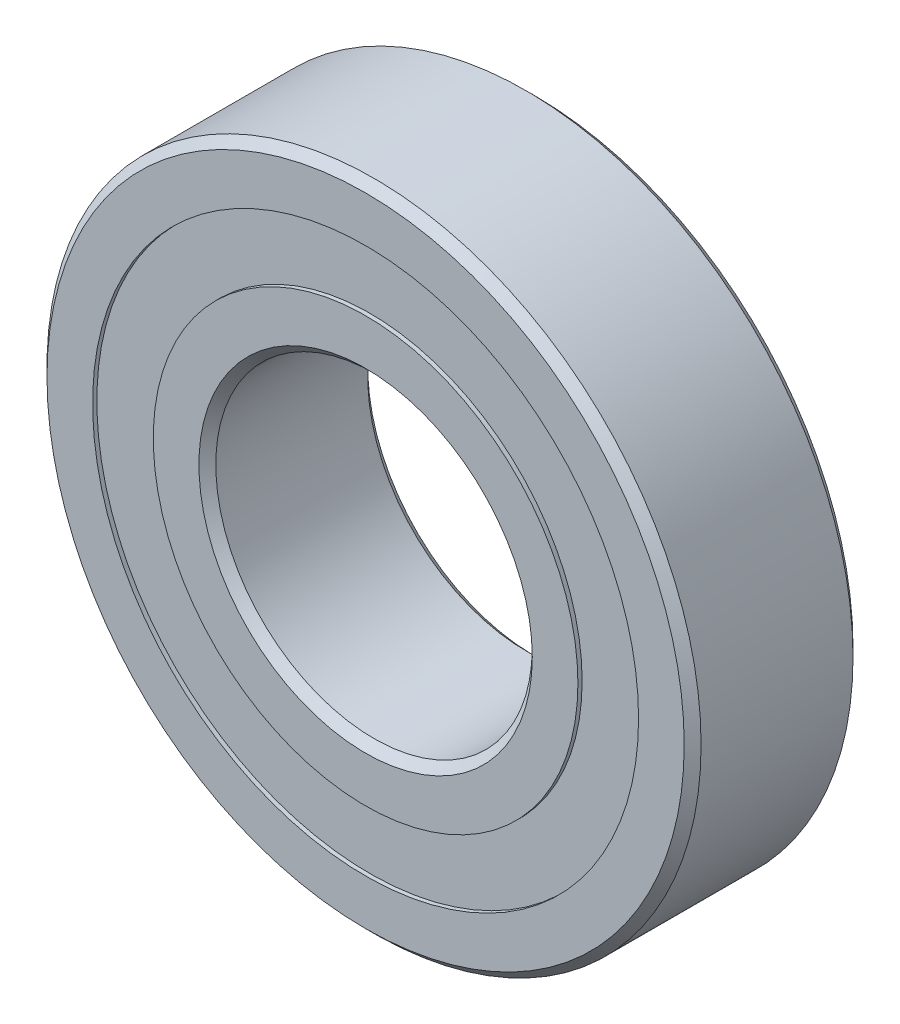
SolidWorks part; units mm, degrees
ref_plane "Front Plane" through (0, 0, 0) normal (0, 0, 1) x (1, 0, 0)
ref_plane "Top Plane" through (0, 0, 0) normal (0, 1, 0) x (1, 0, 0)
ref_plane "Right Plane" through (0, 0, 0) normal (1, 0, 0) x (0, 0, -1)
sketch "Sketch1" plane through (0, 0, 0) normal (0, 0, 1) x (1, 0, 0)
  circle A0 centre (0, 0) radius 31 construction
  circle A1 centre (0, 0) radius 15 construction
  dimension "OD" = 62
  dimension "ID" = 30
sketch "Sketch2" plane through (0, 0, 0) normal (1, 0, 0) x (0, 0, -1)
  line L0 (-8, 0) -> (8, 0) construction
  line L1 (0, 31) -> (0, -31) construction
  line L2 (7.2, 31) -> (-7.2, 31) construction
  line L3 (-7.2, 31) -> (-8, 30.2) construction
  line L4 (-8, 30.2) -> (-8, 25.875) construction
  line L5 (-8, 25.875) -> (-3.5556, 25.875) construction
  line L6 (8, 25.875) -> (3.5556, 25.875) construction
  line L7 (8, 30.2) -> (8, 25.875) construction
  line L8 (7.2, 31) -> (8, 30.2) construction
  line L9 (0, 31) -> (0, 23) construction
  line L10 (0, 23) -> (0, 15) construction
  line L11 (8, 23) -> (-8, 23) construction
  line L12 (-8, 15.8) -> (-8, 20.125) construction
  line L13 (-7.2, 15) -> (-8, 15.8) construction
  line L14 (7.2, 15) -> (-7.2, 15) construction
  line L15 (7.2, 15) -> (8, 15.8) construction
  line L16 (8, 15.8) -> (8, 20.125) construction
  line L17 (8, 20.125) -> (3.5556, 20.125) construction
  line L18 (-8, 20.125) -> (-3.5556, 20.125) construction
  line L19 (-8, 15) -> (-8, -15) construction
  line L20 (8, 31) -> (8, -31) construction
  arc A0 (-3.5556, 25.875) -> (3.5556, 25.875) centre (0, 23) cw construction
  arc A1 (-3.5556, 20.125) -> (3.5556, 20.125) centre (0, 23) ccw construction
  point P14 (0, 15)
  point P18 (0, 23)
  dimension "Approx. Ball Dia." = 9.145
  dimension "D1" = 45
  dimension "D2" = 0.8
  dimension "D3" = 7.1111
  dimension "D4" = 2.875
  dimension "Width" = 16
  dimension "For Shaft Diameter" = 30
  dimension "For Housing ID" = 62
sketch "Sketch3" plane through (0, 0, 0) normal (1, 0, 0) x (0, 0, -1)
  line L0 (-8, 30.2) -> (-8, 25.875) construction
  line L1 (-7.2, 31) -> (-8, 30.2) construction
  line L2 (7.2, 31) -> (-7.2, 31) construction
  line L3 (7.2, 31) -> (8, 30.2) construction
  line L4 (8, 30.2) -> (8, 25.875) construction
  line L5 (8, 25.875) -> (3.5556, 25.875) construction
  line L6 (-8, 25.875) -> (-3.5556, 25.875) construction
  line L7 (-8, 30.2) -> (-8, 25.875)
  line L8 (-7.2, 31) -> (-8, 30.2)
  line L9 (7.2, 31) -> (-7.2, 31)
  line L10 (7.2, 31) -> (8, 30.2)
  line L11 (8, 30.2) -> (8, 25.875)
  line L12 (8, 25.875) -> (3.5556, 25.875)
  line L13 (-8, 25.875) -> (-3.5556, 25.875)
  line L14 (-8, 15.8) -> (-8, 20.125) construction
  line L15 (-7.2, 15) -> (-8, 15.8) construction
  line L16 (7.2, 15) -> (-7.2, 15) construction
  line L17 (7.2, 15) -> (8, 15.8) construction
  line L18 (8, 15.8) -> (8, 20.125) construction
  line L19 (8, 20.125) -> (3.5556, 20.125) construction
  line L20 (-8, 20.125) -> (-3.5556, 20.125) construction
  line L21 (-8, 15.8) -> (-8, 20.125)
  line L22 (-7.2, 15) -> (-8, 15.8)
  line L23 (7.2, 15) -> (-7.2, 15)
  line L24 (7.2, 15) -> (8, 15.8)
  line L25 (8, 15.8) -> (8, 20.125)
  line L26 (8, 20.125) -> (3.5556, 20.125)
  line L27 (-8, 20.125) -> (-3.5556, 20.125)
  arc A0 (3.5556, 25.875) -> (-3.5556, 25.875) centre (0, 23) ccw construction
  arc A1 (3.5556, 25.875) -> (-3.5556, 25.875) centre (0, 23) ccw
  arc A2 (-3.5556, 20.125) -> (3.5556, 20.125) centre (0, 23) ccw construction
  arc A3 (-3.5556, 20.125) -> (3.5556, 20.125) centre (0, 23) ccw
revolve "Revolve1" add sketch "Sketch3" angle 360 about L0
sketch "Sketch4" plane through (0, 0, 0) normal (1, 0, 0) x (0, 0, -1)
  line L0 (-4.5725, 23) -> (4.5725, 23)
  arc A2 (-4.5725, 23) -> (4.5725, 23) centre (0, 23) cw
  arc A3 (3.5556, 25.875) -> (-3.5556, 25.875) centre (0, 23) ccw construction
revolve "Revolve2" add sketch "Sketch4" angle 360 about L0
pattern_circular "CirPattern1" count 11 over 360 about axis through (0, 0, 0) along (0, 0, 1) of bodies 104
sketch "Sketch5" plane through (0, 0, 0) normal (1, 0, 0) x (0, 0, -1)
  line L0 (-8, 25.875) -> (-3.5556, 25.875) construction
  line L1 (-7.6, 25.875) -> (-4.5725, 25.875)
  line L2 (-7.6, 25.875) -> (-7.6, 20.125)
  line L3 (-7.6, 20.125) -> (-4.5725, 20.125)
  line L4 (-4.5725, 25.875) -> (-4.5725, 20.125)
  line L6 (8, 25.875) -> (3.5556, 25.875) construction
  line L7 (7.6, 25.875) -> (4.5725, 25.875)
  line L8 (7.6, 25.875) -> (7.6, 20.125)
  line L9 (7.6, 20.125) -> (4.5725, 20.125)
  line L10 (4.5725, 25.875) -> (4.5725, 20.125)
  line L12 (-7.2, 31) -> (-8, 30.2) construction
  line L13 (-8, 20.125) -> (-3.5556, 20.125) construction
  line L14 (8, 20.125) -> (3.5556, 20.125) construction
  point P18 (-7.6, 30.6)
revolve "Revolve3" add sketch "Sketch5" angle 360 about L0
equation "\"D2@Sketch2\"= \"Width@Sketch2\" * .05"
equation "\"D3@Sketch2\"=\"Width@Sketch2\" / 2.25"
equation "\"D4@Sketch2\"=( \"OD@Sketch1\" - \"Width@Sketch2\" ) *.5 *.125"
equation "\"Approx. No. of Balls\"= ( pi * \"OD@Sketch1\" ) * .5 / \"Approx. Ball Dia.@Sketch2\""
equation "\"Balls@CirPattern1\"=\"Approx. No. of Balls\""
